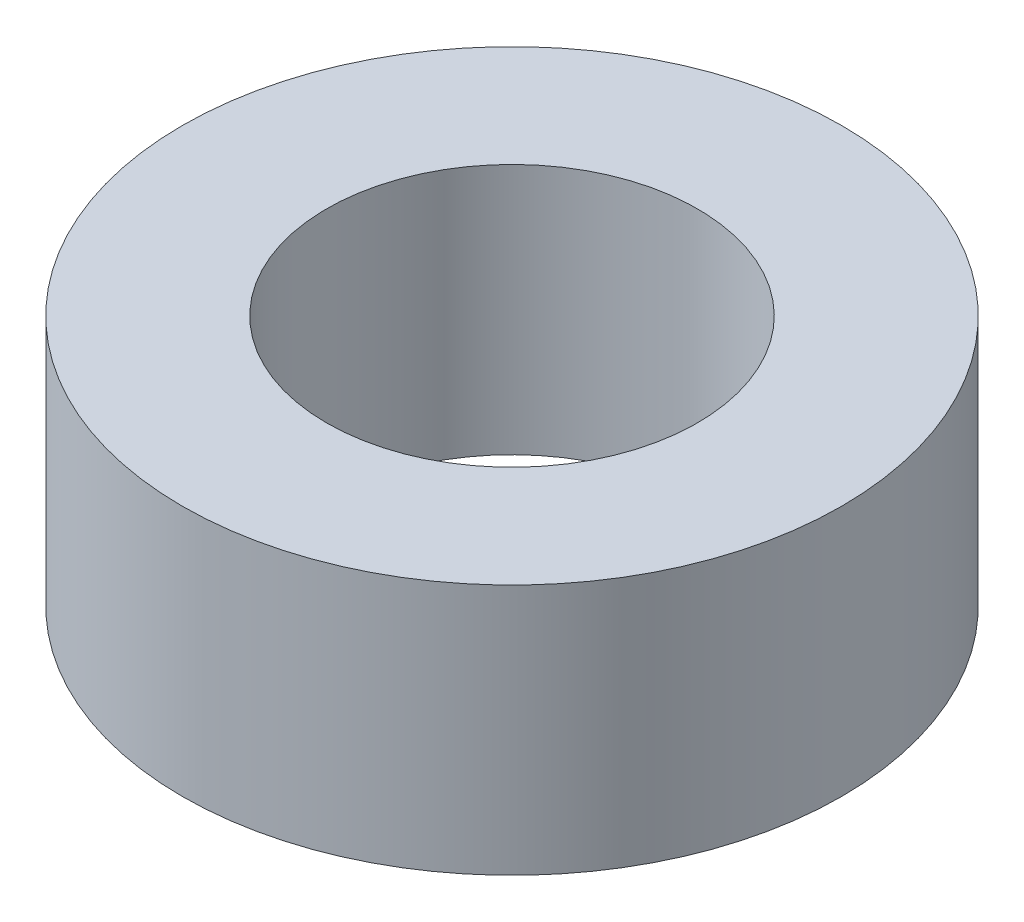
SolidWorks part; units mm, degrees
ref_plane "前视基准面" through (0, 0, 0) normal (0, 0, 1) x (1, 0, 0)
ref_plane "上视基准面" through (0, 0, 0) normal (0, 1, 0) x (1, 0, 0)
ref_plane "右视基准面" through (0, 0, 0) normal (1, 0, 0) x (0, 0, -1)
sketch "草图1" plane through (0, 0, 0) normal (0, 1, 0) x (1, 0, 0)
  circle A0 centre (0, 0) radius 4.5
  circle A1 centre (0, 0) radius 8
  dimension "D1" = 9
  dimension "D2" = 16
extrude "凸台-拉伸1" add sketch "草图1" along normal blind 6.1
